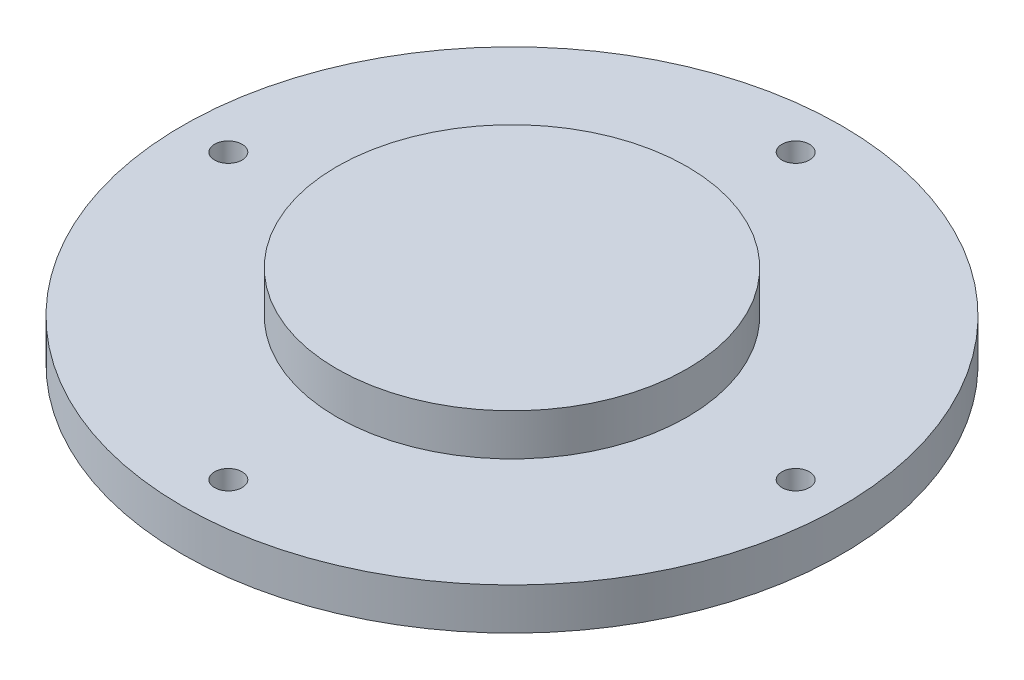
SolidWorks part; units mm, degrees
ref_plane "Front" through (0, 0, 0) normal (0, 0, 1) x (1, 0, 0)
ref_plane "Top" through (0, 0, 0) normal (0, 1, 0) x (1, 0, 0)
ref_plane "Side" through (0, 0, 0) normal (1, 0, 0) x (0, 0, -1)
sketch "Sketch2" plane through (0, 0, 0) normal (0, 0, 1) x (1, 0, 0)
  line L0 (0, 0) -> (0, 48.8324) construction
  line L1 (0, 0) -> (-39.5, 0)
  line L2 (-39.5, 0) -> (-39.5, 5)
  line L3 (-39.5, 5) -> (-21, 5)
  line L4 (-21, 5) -> (-21, 10)
  line L5 (-21, 10) -> (0, 10)
  line L6 (0, 10) -> (0, 0)
  line L7 (-16, 0) -> (-16, 5)
  line L8 (-16, 5) -> (0, 5)
  point P10 (-21, 7.5)
  dimension "D1" = 39.5
  dimension "D2" = 42
  dimension "D3" = 32
  dimension "D4" = 5
  dimension "D5" = 5
  dimension "D6" = 5
revolve "Revolve1" add sketch "Sketch2" angle 360 about L0
sketch "Sketch3" plane through (0, 0, 0) normal (0, -1, 0) x (1, 0, 0)
  circle A0 centre (0, 0) radius 19.5
  circle A1 centre (0, 0) radius 22.5
  dimension "D3" = 45
  dimension "D4" = 45
  dimension "D5" = 39
extrude "Cut-Extrude3" cut sketch "Sketch3" against normal blind 1.68 contours A1 | A0
sketch "Sketch4" plane through (0, 0, 0) normal (0, -1, 0) x (-1, 0, 0)
  circle A0 centre (0, 0) radius 25.5
  circle A1 centre (0, 0) radius 28
  dimension "D1" = 56
  dimension "D2" = 51
extrude "Cut-Extrude4" cut sketch "Sketch4" against normal blind 2.45 contours A1 | A0
sketch "Sketch6" plane through (0, 0, 0) normal (0, -1, 0) x (-1, 0, 0)
  circle A0 centre (0, 0) radius 34
  dimension "D1" = 68
hole_wizard "M4x0.7 Tapped Hole1" positions "Sketch7" profile "Sketch8" tap size "M4x0.7" standard "ANSI Metric" end condition through all
sketch "Sketch7" plane through (0, 0, 0) normal (0, -1, 0) x (-1, 0, 0)
  circle A0 centre (0, 0) radius 34 construction
  point P0 (0, -34)
sketch "Sketch8" plane through (0, 0, 34) normal (1, 0, 0) x (0, 0, -1)
  line L0 (0, 0) -> (0, 10)
  line L1 (0, 10) -> (1.65, 10)
  line L2 (1.65, 10) -> (1.65, 0)
  line L5 (1.65, 0) -> (0, 0)
  line L11 (0, -6.35) -> (0, 107.95) construction
  dimension "Thru Tap Drill Dia." = 3.3
  dimension "Thru Tap Drill Depth" = 10
cosmetic thread "Hole Thread1" parameters "D2"=4
pattern_circular "CirPattern1" count 4 over 360 about axis through (0, 0, 0) along (0, 1, 0) of "M4x0.7 Tapped Hole1"
